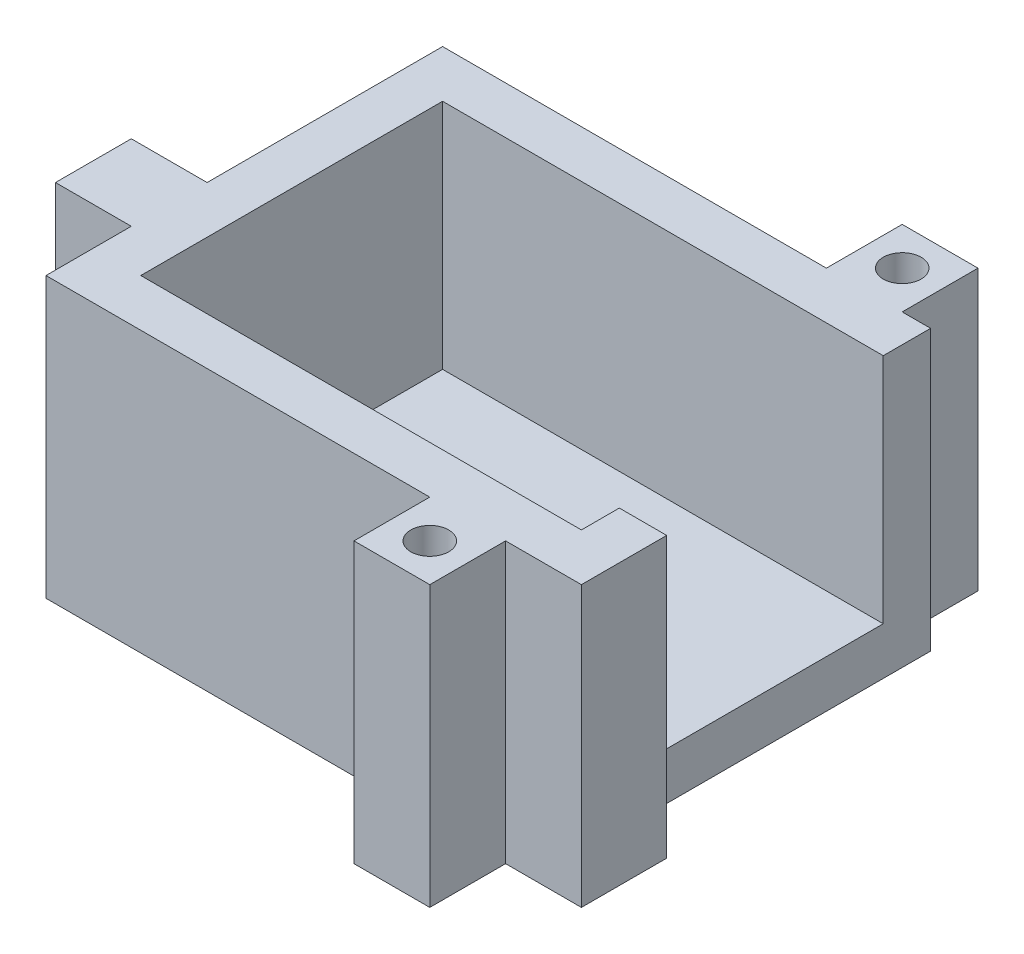
SolidWorks part; units mm, degrees
ref_plane "Front Plane" through (0, 0, 0) normal (0, 0, 1) x (1, 0, 0)
ref_plane "Top Plane" through (0, 0, 0) normal (0, 1, 0) x (1, 0, 0)
ref_plane "Right Plane" through (0, 0, 0) normal (1, 0, 0) x (0, 0, -1)
sketch "Sketch1" plane through (0, 0, 0) normal (0, 1, 0) x (1, 0, 0)
  line L17 (0, 0) -> (51.5, 0)
  line L18 (51.5, 0) -> (51.5, -5)
  line L19 (51.5, -5) -> (5, -5)
  line L20 (5, -5) -> (5, -36.85)
  line L21 (5, -36.85) -> (51.5, -36.85)
  line L22 (51.5, -36.85) -> (51.5, -32.85)
  line L23 (51.5, -32.85) -> (56.5, -32.85)
  line L24 (56.5, -32.85) -> (56.5, -41.85)
  line L25 (56.5, -41.85) -> (0, -41.85)
  line L26 (0, -41.85) -> (0, 0)
  dimension "D1" = 31.85
  dimension "D2" = 5
  dimension "D3" = 5
  dimension "D4" = 5
  dimension "D5" = 5
  dimension "D6" = 51.5
  dimension "D7" = 56.5
  dimension "D8" = 4
extrude "Boss-Extrude1" add sketch "Sketch1" along normal blind 24.5
sketch "Sketch2" plane through (0, 0, 0) normal (0, -1, 0) x (1, 0, 0)
  line L1 (0, 41.85) -> (103, 41.85)
  line L2 (0, 41.85) -> (0, 0)
  line L3 (0, 0) -> (103, 0)
  line L4 (103, 41.85) -> (103, 0)
  dimension "D1" = 103
extrude "Boss-Extrude2" add sketch "Sketch2" along normal blind 5
sketch "Sketch3" plane through (0, 0, 0) normal (0, 1, 0) x (1, 0, 0)
  line L0 (56.5, -32.85) -> (51.5, -32.85) construction
  line L1 (51.5, -5) -> (98, -5)
  line L2 (51.5, -5) -> (51.5, -32.85)
  line L3 (51.5, -32.85) -> (98, -32.85)
  line L4 (98, -5) -> (98, -32.85)
  line L6 (103, 0) -> (103, -41.85) construction
  dimension "D1" = 0
  dimension "D2" = 5
extrude "Cut-Extrude1" cut sketch "Sketch3" against normal blind 26
sketch "Sketch4" plane through (0, 0, 41.85) normal (0, 0, 1) x (1, 0, 0)
  line L1 (0, -5) -> (8, -5)
  line L2 (0, -5) -> (0, -2)
  line L3 (0, -2) -> (8, -2)
  line L4 (8, -5) -> (8, -2)
  dimension "D1" = 3
  dimension "D2" = 8
sketch "Sketch7" plane through (0, 0, 41.85) normal (0, 0, 1) x (1, 0, 0)
  line L1 (0, -2) -> (8, -2)
  line L2 (0, -2) -> (0, -5)
  line L3 (0, -5) -> (8, -5)
  line L4 (8, -2) -> (8, -5)
extrude "Boss-Extrude3" add sketch "Sketch7" along normal blind 8
sketch "Sketch8" plane through (0, -2, 0) normal (0, 1, 0) x (1, 0, 0)
  line L0 (8, -49.85) -> (8, -41.85) construction
  line L1 (0, -41.85) -> (8, -41.85) construction
  circle A0 centre (4, -45.85) radius 2.5
  dimension "D1" = 5
  dimension "D2" = 4
  dimension "D3" = 4
extrude "Cut-Extrude2" cut sketch "Sketch8" against normal blind 8
sketch "Sketch9" plane through (0, 0, 0) normal (0, 0, -1) x (-1, 0, 0)
  line L1 (-103, -5) -> (-95, -5)
  line L2 (-103, -5) -> (-103, -2)
  line L3 (-103, -2) -> (-95, -2)
  line L4 (-95, -5) -> (-95, -2)
  dimension "D1" = 3
  dimension "D2" = 8
extrude "Boss-Extrude4" add sketch "Sketch9" along normal blind 8
sketch "Sketch10" plane through (0, -2, 0) normal (0, 1, 0) x (1, 0, 0)
  line L0 (103, 8) -> (103, 0) construction
  line L1 (95, 8) -> (103, 8) construction
  circle A0 centre (99, 3.9967) radius 2.5
  dimension "D1" = 5
  dimension "D2" = 4
  dimension "D3" = 4.0033
extrude "Cut-Extrude3" cut sketch "Sketch10" against normal blind 8
sketch "Sketch12" plane through (0, 0, 0) normal (0, 1, 0) x (1, 0, 0)
  line L0 (98, -5) -> (51.5, -5) construction
  line L1 (95, -5) -> (83.5, -5)
  line L2 (95, -5) -> (95, 0)
  line L3 (95, 0) -> (83.5, 0)
  line L4 (83.5, -5) -> (83.5, 0)
  line L5 (51.5, 0) -> (103, 0) construction
  line L6 (95, 8) -> (95, 0) construction
  line L7 (51.5, -5) -> (51.5, 0) construction
  dimension "D1" = 0
  dimension "D2" = 32
extrude "Cut-Extrude4" cut sketch "Sketch12" against normal blind 8
sketch "Sketch14" plane through (0, 0, 0) normal (0, 0, -1) x (-1, 0, 0)
  line L1 (-83.5, -5) -> (-75.5, -5)
  line L2 (-83.5, -5) -> (-83.5, -2)
  line L3 (-83.5, -2) -> (-75.5, -2)
  line L4 (-75.5, -5) -> (-75.5, -2)
  dimension "D1" = 8
  dimension "D2" = 3
extrude "Boss-Extrude5" add sketch "Sketch14" along normal blind 8
sketch "Sketch15" plane through (0, -2, 0) normal (0, 1, 0) x (1, 0, 0)
  line L0 (75.5, 8) -> (83.5, 8) construction
  line L1 (83.5, 8) -> (83.5, 0) construction
  circle A0 centre (79.5, 4) radius 2.5
  dimension "D1" = 5
  dimension "D2" = 4
  dimension "D3" = 4
extrude "Cut-Extrude5" cut sketch "Sketch15" against normal blind 8
sketch "Sketch16" plane through (0, 0, 0) normal (0, 0, -1) x (-1, 0, 0)
  line L12 (-51.5, 24.5) -> (0, 24.5) construction
  line L17 (-48.5, 24.5) -> (-40.5, 24.5)
  line L18 (-48.5, 24.5) -> (-48.5, -5)
  line L19 (-48.5, -5) -> (-40.5, -5)
  line L20 (-40.5, 24.5) -> (-40.5, -5)
  line L21 (0, -5) -> (-75.5, -5) construction
  line L22 (-51.5, 24.5) -> (-51.5, 0) construction
  dimension "D1" = 8
  dimension "D2" = 3
extrude "Boss-Extrude6" add sketch "Sketch16" along normal blind 8
sketch "Sketch17" plane through (0, 0, 41.85) normal (0, 0, 1) x (1, 0, 0)
  line L0 (0, 24.5) -> (56.5, 24.5) construction
  line L1 (48.5, 24.5) -> (34.5, 24.5)
  line L2 (48.5, 24.5) -> (48.5, -5)
  line L3 (48.5, -5) -> (34.5, -5)
  line L4 (34.5, 24.5) -> (34.5, -5)
  line L5 (103, -5) -> (8, -5) construction
  line L6 (56.5, 24.5) -> (56.5, 0) construction
  dimension "D1" = 8
  dimension "D2" = 14
extrude "Boss-Extrude7" add sketch "Sketch17" along normal blind 8
sketch "Sketch18" plane through (0, 24.5, 0) normal (0, 1, 0) x (1, 0, 0)
  line L0 (48.5, 8) -> (48.5, 0) construction
  line L2 (40.5, 8) -> (48.5, 8) construction
  line L3 (48.5, -49.85) -> (48.5, -41.85) construction
  line L4 (48.5, -49.85) -> (34.5, -49.85) construction
  circle A0 centre (44.5, 4) radius 2
  circle A1 centre (44.5, -45.85) radius 2
  dimension "D5" = 4
  dimension "D6" = 4
  dimension "D1" = 4
  dimension "D2" = 4
  dimension "D3" = 4
  dimension "D4" = 4
extrude "Cut-Extrude6" cut sketch "Sketch18" against normal blind 10
sketch "Sketch19" plane through (34.5, 0, 0) normal (-1, 0, 0) x (0, 0, 1)
  line L1 (41.85, 24.5) -> (49.85, 24.5)
  line L2 (41.85, 24.5) -> (41.85, -5)
  line L3 (41.85, -5) -> (49.85, -5)
  line L4 (49.85, 24.5) -> (49.85, -5)
extrude "Boss-Extrude8" add sketch "Sketch19" along normal blind 8
sketch "Sketch20" plane through (0, 24.5, 0) normal (0, 1, 0) x (1, 0, 0)
  line L2 (51.5, -36.85) -> (5, -36.85) construction
  line L7 (26.5, -49.85) -> (39.5, -49.85)
  line L8 (26.5, -49.85) -> (26.5, -36.85)
  line L9 (26.5, -36.85) -> (39.5, -36.85)
  line L10 (39.5, -49.85) -> (39.5, -36.85)
  dimension "D1" = 13
extrude "Boss-Extrude9" add sketch "Sketch20" along normal blind 88
sketch "Sketch22" plane through (0, 0, 0) normal (0, 1, 0) x (1, 0, 0)
  line L1 (103, 8) -> (51.5, 8)
  line L2 (103, 8) -> (103, -32.85)
  line L3 (103, -32.85) -> (51.5, -32.85)
  line L4 (51.5, 8) -> (51.5, -32.85)
  line L5 (103, -32.85) -> (56.5, -32.85)
  line L6 (103, -32.85) -> (103, -41.85)
  line L7 (103, -41.85) -> (56.5, -41.85)
  line L8 (56.5, -32.85) -> (56.5, -41.85)
  line M1 (103, 0) -> (95, 0)
  line M2 (95, 0) -> (95, -5)
  line M3 (95, -5) -> (98, -5)
  line M4 (98, -5) -> (98, -32.85)
  line M5 (98, -32.85) -> (56.5, -32.85)
  line M6 (56.5, -32.85) -> (56.5, -41.85)
  line M7 (56.5, -41.85) -> (103, -41.85)
  line M8 (103, -41.85) -> (103, 0)
extrude "Cut-Extrude8" cut sketch "Sketch22" against normal blind 48 contours L1 L4 L3 L2 M5 M4 M3 M2 M1 | L3 M8 M5 M6 M7 | L3 M8 M1 M2 M3 M4
sketch "Sketch23" plane through (0, -5, 0) normal (0, -1, 0) x (1, 0, 0)
  line L1 (48.5, 0) -> (40.5, 0)
  line L2 (48.5, 0) -> (48.5, -8)
  line L3 (48.5, -8) -> (40.5, -8)
  line L4 (40.5, 0) -> (40.5, -8)
  circle A0 centre (44.5, -4) radius 2.5
  dimension "D1" = 5
  dimension "D2" = 4
  dimension "D3" = 4
extrude "Cut-Extrude9" cut sketch "Sketch23" against normal blind 10 contours A0
sketch "Sketch25" plane through (0, 0, 49.85) normal (0, 0, 1) x (1, 0, 0)
  line L1 (0, -5) -> (8, -5)
  line L2 (0, -5) -> (0, -2)
  line L3 (0, -2) -> (8, -2)
  line L4 (8, -5) -> (8, -2)
extrude "Cut-Extrude10" cut sketch "Sketch25" against normal blind 8
sketch "Sketch27" plane through (0, 0, 0) normal (-1, 0, 0) x (0, 0, 1)
  line L0 (0, 24.5) -> (41.85, 24.5) construction
  line L1 (32.85, 24.5) -> (24.85, 24.5)
  line L2 (32.85, 24.5) -> (32.85, -5)
  line L3 (32.85, -5) -> (24.85, -5)
  line L4 (24.85, 24.5) -> (24.85, -5)
  line L5 (41.85, -5) -> (0, -5) construction
  line L6 (36.85, 112.5) -> (36.85, 24.5) construction
  dimension "D1" = 8
  dimension "D2" = 4
extrude "Boss-Extrude11" add sketch "Sketch27" along normal blind 8
sketch "Sketch28" plane through (0, -5, 0) normal (0, -1, 0) x (1, 0, 0)
  line L0 (-8, 24.85) -> (-8, 32.85) construction
  line L1 (-8, 32.85) -> (0, 32.85) construction
  circle A1 centre (-4, 28.85) radius 2.5
  dimension "D1" = 4
  dimension "D3" = 5
  dimension "D2" = 4
extrude "Cut-Extrude12" cut sketch "Sketch28" against normal blind 15
sketch "Sketch29" plane through (0, 112.5, 0) normal (0, 1, 0) x (1, 0, 0)
  line L1 (26.5, -49.85) -> (39.5, -49.85)
  line L2 (26.5, -49.85) -> (26.5, -36.85)
  line L3 (26.5, -36.85) -> (39.5, -36.85)
  line L4 (39.5, -49.85) -> (39.5, -36.85)
extrude "Cut-Extrude13" cut sketch "Sketch29" against normal up to surface (88 mm away) up to face at (44.5, 24.5, 47.85)
sketch "Sketch30" plane through (0, -5, 0) normal (0, -1, 0) x (1, 0, 0)
  line L0 (48.5, 49.85) -> (48.5, 41.85) construction
  line L1 (26.5, 49.85) -> (40.5, 49.85)
  line L2 (26.5, 49.85) -> (26.5, 41.85)
  line L3 (26.5, 41.85) -> (40.5, 41.85)
  line L4 (40.5, 49.85) -> (40.5, 41.85)
  line L5 (26.5, 41.85) -> (0, 41.85) construction
  dimension "D1" = 8
  dimension "D2" = 0
extrude "Cut-Extrude14" cut sketch "Sketch30" against normal blind 147
